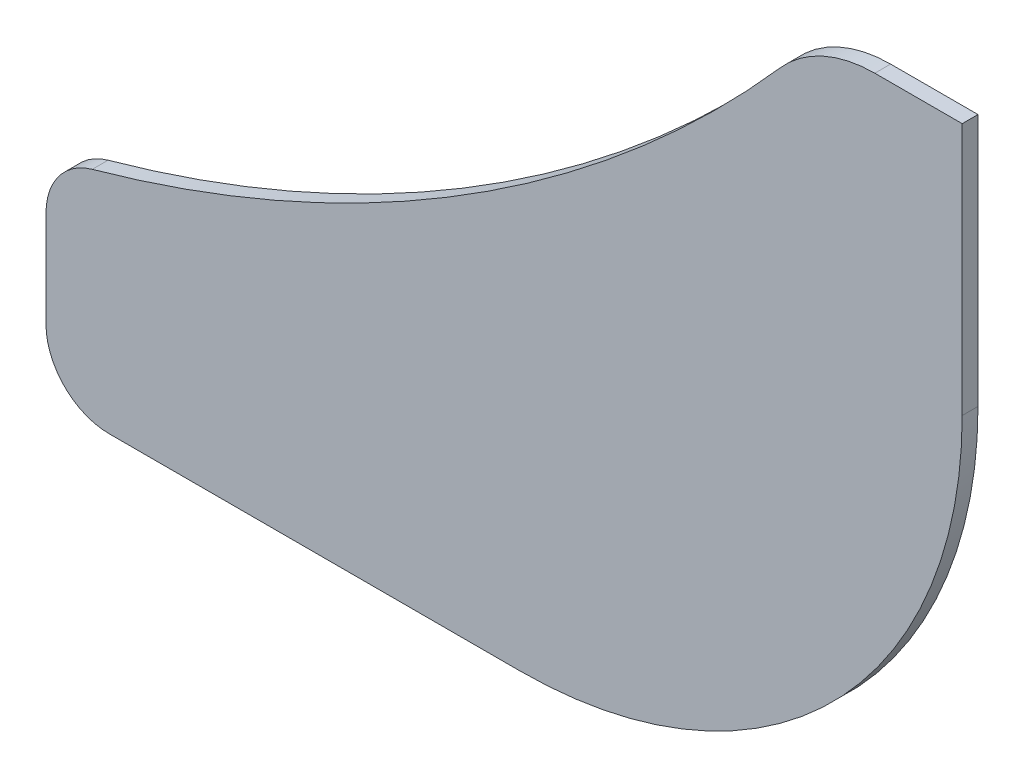
SolidWorks part; units mm, degrees
ref_plane "Front Plane" through (0, 0, 0) normal (0, 0, 1) x (1, 0, 0)
ref_plane "Top Plane" through (0, 0, 0) normal (0, 1, 0) x (1, 0, 0)
ref_plane "Right Plane" through (0, 0, 0) normal (1, 0, 0) x (0, 0, -1)
sketch "Sketch1" plane through (0, 0, 0) normal (0, 0, 1) x (1, 0, 0)
  line L15 (771.9038, 126.6023) -> (771.9038, 164.7023)
  line L17 (203.2, -203.2) -> (203.2, -261.62)
  line L20 (0, 0) -> (82.8917, 0) construction
  line L21 (0, 0) -> (0, -86.4487) construction
  line L22 (771.9038, 126.6023) -> (907.5478, 126.6023) construction
  line L25 (571.4712, -109.22) -> (571.4712, -7.62)
  line L26 (228.6, -287.02) -> (393.6712, -287.02)
  line L27 (312.4515, -206.6231) -> (466.4308, -117.7231) construction
  line L28 (451.8433, -111.2042) -> (546.0712, -26.0566) construction
  line L29 (571.4712, -7.62) -> (536.3464, -7.62)
  line L40 (361.6164, -231.6548) -> (133.988, -252.7091) construction
  line L41 (157.3315, -273.5734) -> (-70.4948, -254.7805) construction
  arc A5 (203.2, -261.62) -> (228.6, -287.02) centre (228.6, -261.62) ccw
  arc A6 (203.2, -203.2) -> (498.1985, -24.8733) centre (68.2384, 353.2267) ccw
  arc A7 (571.4712, -109.22) -> (393.6712, -287.02) centre (393.6712, -109.22) cw
  arc A8 (536.3464, -7.62) -> (498.1985, -24.8733) centre (536.3464, -58.42) ccw
  spline S0 degree 3 poles (360.3362, -232.1476) (361.944, -231.5594) (360.2733, -231.9279) (358.8705, -232.1286) (355.491, -232.7497) (351.3118, -233.4654) (345.8288, -234.3937) (339.3319, -235.4503) (331.8137, -236.6267) (323.3898, -237.8749) (314.1481, -239.1645) (304.196, -240.4529) (293.645, -241.7102) (282.6109, -242.9031) (271.2144, -244.0118) (259.5796, -245.0173) (247.8327, -245.923) (236.1052, -246.7089) (224.5878, -247.4466) (213.3874, -247.9449) (202.6055, -248.1613) (192.2857, -248.184) (182.5214, -248.0635) (173.413, -247.8762) (165.0492, -247.6957) (157.5243, -247.5827) (150.9198, -247.5968) (145.3176, -247.8045) (140.7752, -248.2212) (137.3462, -248.9332) (134.9534, -249.8477) (133.6053, -251.5229) (134.1931, -253.5982) (136.0729, -255.3852) (139.0627, -257.3468) (143.3055, -259.3644) (148.7486, -261.4241) (155.3647, -263.3995) (163.0752, -265.2124) (171.7927, -266.7481) (181.4066, -267.9166) (191.7956, -268.6246) (202.8233, -268.8006) (214.344, -268.4024) (226.142, -267.3648) (238.0677, -265.8064) (250.0128, -263.9526) (261.9011, -261.7778) (273.6057, -259.3395) (284.9982, -256.6886) (295.9553, -253.8811) (306.362, -250.9812) (316.1121, -248.0592) (325.1026, -245.1817) (333.2481, -242.4287) (340.4703, -239.8598) (346.6777, -237.559) (351.8912, -235.562) (355.8426, -233.9905) (359.046, -232.7314) (360.3362, -232.1476) (361.944, -231.5594) (360.2733, -231.9279) knots -0.012273 -0.005484 -0.001375 0 0.001366 0.005489 0.012269 0.02165 0.033497 0.04769 0.06403 0.082338 0.102396 0.123959 0.146791 0.170641 0.19524 0.220332 0.245646 0.27091 0.295825 0.31977 0.342911 0.365083 0.386049 0.405629 0.423597 0.43978 0.453966 0.466008 0.475784 0.483219 0.48846 0.492078 0.495706 0.500976 0.508553 0.518608 0.53108 0.545907 0.56292 0.581928 0.60273 0.625094 0.648778 0.673537 0.699099 0.724814 0.750772 0.776731 0.802428 0.827555 0.851851 0.875071 0.896936 0.917223 0.935694 0.952169 0.966419 0.978318 0.987727 0.994516 0.998625 1 1.001366 1.005489 1.012269 only from (347.4667, -231.1805) to (347.4667, -231.1805) construction
  spline S1 degree 3 poles (155.9851, -273.8364) (157.6707, -273.5362) (155.9614, -273.6091) (154.545, -273.5632) (151.109, -273.588) (146.869, -273.5671) (141.3082, -273.5292) (134.7264, -273.4415) (127.1182, -273.2946) (118.6055, -273.0609) (109.2803, -272.7261) (99.2556, -272.2668) (88.6466, -271.6729) (77.573, -270.9316) (66.1571, -270.0445) (54.5244, -269.0143) (42.7988, -267.8665) (31.1129, -266.6039) (19.6424, -265.3305) (8.5257, -263.8763) (-2.1301, -262.2171) (-12.2969, -260.4475) (-21.892, -258.6332) (-30.8295, -256.8671) (-39.0349, -255.237) (-46.4259, -253.8191) (-52.9324, -252.6861) (-58.4856, -251.9178) (-63.0313, -251.5394) (-66.5319, -251.6451) (-69.0472, -252.1302) (-70.6657, -253.5459) (-70.4472, -255.6917) (-68.9062, -257.778) (-66.3025, -260.229) (-62.4745, -262.9527) (-57.4718, -265.9263) (-51.2992, -269.0205) (-44.0206, -272.1448) (-35.7023, -275.171) (-26.4373, -277.9912) (-16.3291, -280.4924) (-5.4995, -282.5807) (5.9153, -284.1891) (17.7142, -285.2159) (29.7294, -285.7521) (41.8149, -286.0007) (53.9003, -285.9233) (65.8505, -285.5546) (77.5302, -284.9222) (88.8084, -284.06) (99.5605, -283.0113) (109.6699, -281.8268) (119.0235, -280.5542) (127.5233, -279.2575) (135.0819, -277.9817) (141.5945, -276.7938) (147.0755, -275.7324) (151.2398, -274.8709) (154.6131, -274.1873) (155.9851, -273.8364) (157.6707, -273.5362) (155.9614, -273.6091) knots -0.012273 -0.005484 -0.001375 0 0.001366 0.005489 0.012269 0.02165 0.033497 0.04769 0.06403 0.082338 0.102396 0.123959 0.146791 0.170641 0.19524 0.220332 0.245646 0.27091 0.295825 0.31977 0.342911 0.365083 0.386049 0.405629 0.423597 0.43978 0.453966 0.466008 0.475784 0.483219 0.48846 0.492078 0.495706 0.500976 0.508553 0.518608 0.53108 0.545907 0.56292 0.581928 0.60273 0.625094 0.648778 0.673537 0.699099 0.724814 0.750772 0.776731 0.802428 0.827555 0.851851 0.875071 0.896936 0.917223 0.935694 0.952169 0.966419 0.978318 0.987727 0.994516 0.998625 1 1.001366 1.005489 1.012269 only from (157.3315, -273.5734) to (157.3315, -273.5734) construction
  spline S3 degree 3 poles (360.3362, -232.1476) (361.944, -231.5594) (360.2733, -231.9279) (358.8705, -232.1286) (355.491, -232.7497) (351.3118, -233.4654) (345.8288, -234.3937) (339.3319, -235.4503) (331.8137, -236.6267) (323.3898, -237.8749) (314.1481, -239.1645) (304.196, -240.4529) (293.645, -241.7102) (282.6109, -242.9031) (271.2144, -244.0118) (259.5796, -245.0173) (247.8327, -245.923) (236.1052, -246.7089) (224.5878, -247.4466) (213.3874, -247.9449) (202.6055, -248.1613) (192.2857, -248.184) (182.5214, -248.0635) (173.413, -247.8762) (165.0492, -247.6957) (157.5243, -247.5827) (150.9198, -247.5968) (145.3176, -247.8045) (140.7752, -248.2212) (137.3462, -248.9332) (134.9534, -249.8477) (133.6053, -251.5229) (134.1931, -253.5982) (136.0729, -255.3852) (139.0627, -257.3468) (143.3055, -259.3644) (148.7486, -261.4241) (155.3647, -263.3995) (163.0752, -265.2124) (171.7927, -266.7481) (181.4066, -267.9166) (191.7956, -268.6246) (202.8233, -268.8006) (214.344, -268.4024) (226.142, -267.3648) (238.0677, -265.8064) (250.0128, -263.9526) (261.9011, -261.7778) (273.6057, -259.3395) (284.9982, -256.6886) (295.9553, -253.8811) (306.362, -250.9812) (316.1121, -248.0592) (325.1026, -245.1817) (333.2481, -242.4287) (340.4703, -239.8598) (346.6777, -237.559) (351.8912, -235.562) (355.8426, -233.9905) (359.046, -232.7314) (360.3362, -232.1476) (361.944, -231.5594) (360.2733, -231.9279) knots -0.012273 -0.005484 -0.001375 0 0.001366 0.005489 0.012269 0.02165 0.033497 0.04769 0.06403 0.082338 0.102396 0.123959 0.146791 0.170641 0.19524 0.220332 0.245646 0.27091 0.295825 0.31977 0.342911 0.365083 0.386049 0.405629 0.423597 0.43978 0.453966 0.466008 0.475784 0.483219 0.48846 0.492078 0.495706 0.500976 0.508553 0.518608 0.53108 0.545907 0.56292 0.581928 0.60273 0.625094 0.648778 0.673537 0.699099 0.724814 0.750772 0.776731 0.802428 0.827555 0.851851 0.875071 0.896936 0.917223 0.935694 0.952169 0.966419 0.978318 0.987727 0.994516 0.998625 1 1.001366 1.005489 1.012269 only from (361.6164, -231.6548) to (361.6164, -231.6548) construction
  spline S8 degree 3 poles (155.9851, -273.8364) (157.6707, -273.5362) (155.9614, -273.6091) (154.545, -273.5632) (151.109, -273.588) (146.869, -273.5671) (141.3082, -273.5292) (134.7264, -273.4415) (127.1182, -273.2946) (118.6055, -273.0609) (109.2803, -272.7261) (99.2556, -272.2668) (88.6466, -271.6729) (77.573, -270.9316) (66.1571, -270.0445) (54.5244, -269.0143) (42.7988, -267.8665) (31.1129, -266.6039) (19.6424, -265.3305) (8.5257, -263.8763) (-2.1301, -262.2171) (-12.2969, -260.4475) (-21.892, -258.6332) (-30.8295, -256.8671) (-39.0349, -255.237) (-46.4259, -253.8191) (-52.9324, -252.6861) (-58.4856, -251.9178) (-63.0313, -251.5394) (-66.5319, -251.6451) (-69.0472, -252.1302) (-70.6657, -253.5459) (-70.4472, -255.6917) (-68.9062, -257.778) (-66.3025, -260.229) (-62.4745, -262.9527) (-57.4718, -265.9263) (-51.2992, -269.0205) (-44.0206, -272.1448) (-35.7023, -275.171) (-26.4373, -277.9912) (-16.3291, -280.4924) (-5.4995, -282.5807) (5.9153, -284.1891) (17.7142, -285.2159) (29.7294, -285.7521) (41.8149, -286.0007) (53.9003, -285.9233) (65.8505, -285.5546) (77.5302, -284.9222) (88.8084, -284.06) (99.5605, -283.0113) (109.6699, -281.8268) (119.0235, -280.5542) (127.5233, -279.2575) (135.0819, -277.9817) (141.5945, -276.7938) (147.0755, -275.7324) (151.2398, -274.8709) (154.6131, -274.1873) (155.9851, -273.8364) (157.6707, -273.5362) (155.9614, -273.6091) knots -0.012273 -0.005484 -0.001375 0 0.001366 0.005489 0.012269 0.02165 0.033497 0.04769 0.06403 0.082338 0.102396 0.123959 0.146791 0.170641 0.19524 0.220332 0.245646 0.27091 0.295825 0.31977 0.342911 0.365083 0.386049 0.405629 0.423597 0.43978 0.453966 0.466008 0.475784 0.483219 0.48846 0.492078 0.495706 0.500976 0.508553 0.518608 0.53108 0.545907 0.56292 0.581928 0.60273 0.625094 0.648778 0.673537 0.699099 0.724814 0.750772 0.776731 0.802428 0.827555 0.851851 0.875071 0.896936 0.917223 0.935694 0.952169 0.966419 0.978318 0.987727 0.994516 0.998625 1 1.001366 1.005489 1.012269 only from (157.3315, -273.5734) to (157.3315, -273.5734) construction
  point P19 (571.4712, -287.02)
  point P39 (157.3315, -273.5734)
  dimension "D2" = 25.4
  dimension "D3" = 203.2
  dimension "D6" = 127
  dimension "D10" = 177.8
  dimension "D11" = 50.8
  dimension "D13" = 38.1
  dimension "D14" = 25.4
  dimension "D4" = 279.4
  dimension "D5" = 83.82
  dimension "D7" = 177.8
  dimension "D8" = 144.2667
  dimension "D9" = 203.2
extrude "Boss-Extrude1" add sketch "Sketch1" along normal blind 6.35
fillet "Fillet1" radius 25.4 1 edges at (203.2, -203.2, 3.175)
